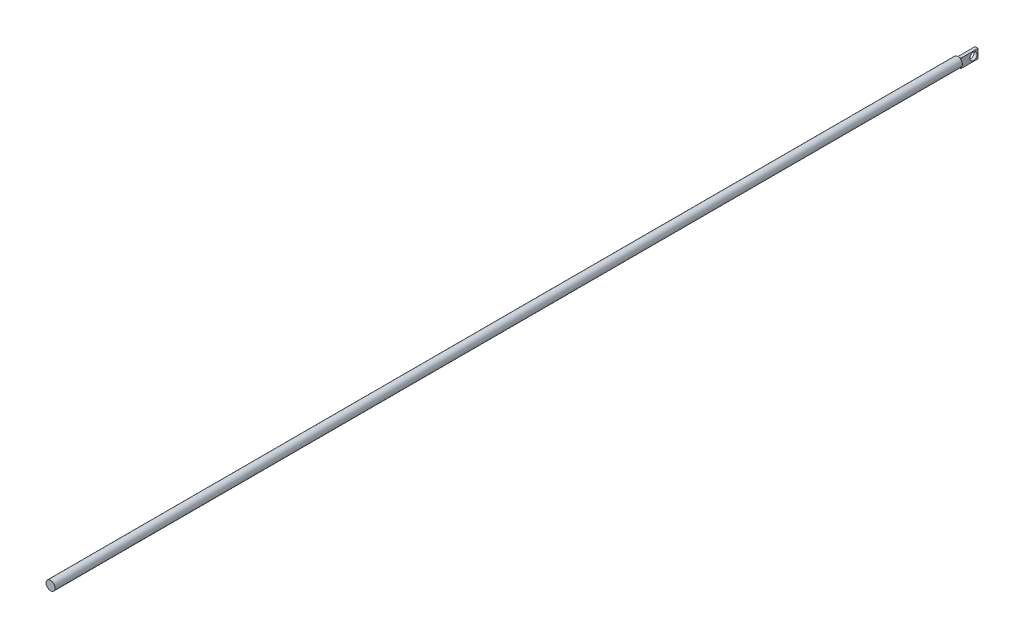
SolidWorks part; units mm, degrees
ref_plane "Ön Düzlem" through (0, 0, 0) normal (0, 0, 1) x (1, 0, 0)
ref_plane "Üst Düzlem" through (0, 0, 0) normal (0, 1, 0) x (1, 0, 0)
ref_plane "Sağ Düzlem" through (0, 0, 0) normal (1, 0, 0) x (0, 0, -1)
sketch "Sketch1" plane through (0, 0, 0) normal (0, 0, 1) x (1, 0, 0)
  circle A0 centre (0, 0) radius 7.5
  dimension "D1" = 15
extrude "Boss-Extrude1" add sketch "Sketch1" along normal blind 1500
sketch "Sketch4" plane through (0, 0, 0) normal (1, 0, 0) x (0, 0, -1)
  line L1 (0.05, 7.415) -> (28.3632, 7.415)
  line L2 (0.05, 7.415) -> (0.05, -7.585)
  line L3 (0.05, -7.585) -> (28.3632, -7.585)
  line L4 (28.3632, 7.415) -> (28.3632, -7.585)
  line L5 (0.05, 7.415) -> (28.3632, -7.585) construction
  line L6 (0.05, -7.585) -> (28.3632, 7.415) construction
  circle A0 centre (21.0732, -0.289) radius 6
  point P4 (14.2066, -0.085)
  dimension "D3" = 12
  dimension "D1" = 15
  dimension "D2" = 28.3132
extrude "Boss-Extrude3" add sketch "Sketch4" along normal blind 5 separate body
